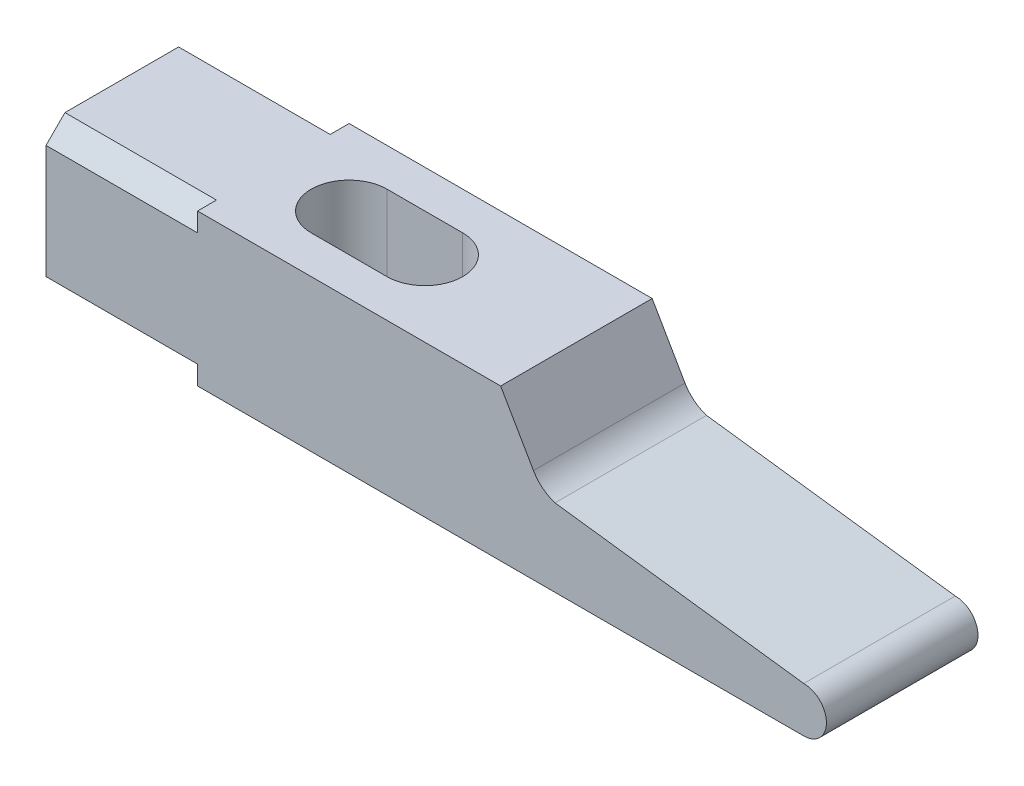
SolidWorks part; units mm, degrees
ref_plane "前视基准面" through (0, 0, 0) normal (0, 0, 1) x (1, 0, 0)
ref_plane "上视基准面" through (0, 0, 0) normal (0, 1, 0) x (1, 0, 0)
ref_plane "右视基准面" through (0, 0, 0) normal (1, 0, 0) x (0, 0, -1)
sketch "草图1" plane through (0, 0, 0) normal (0, 0, 1) x (1, 0, 0)
  line L0 (0, 0) -> (0, 20)
  line L1 (0, 20) -> (60, 20)
  line L2 (60, 20) -> (64.3301, 12.5)
  line L4 (100, 0) -> (0, 0)
  line L6 (67.1731, 10.2263) -> (100, 6)
  arc A0 (67.1731, 10.2263) -> (64.3301, 12.5) centre (68.6603, 15) cw
  arc A1 (100, 6) -> (100, 0) centre (100, 3) cw
  dimension "D5" = 5
  dimension "D1" = 20
  dimension "D2" = 60
  dimension "D3" = 100
  dimension "D4" = 120
  dimension "D6" = 15
extrude "凸台-拉伸1" add sketch "草图1" along normal mid plane 20
sketch "草图2" plane through (0, 20, 0) normal (0, 1, 0) x (1, 0, 0)
  line L0 (30, 0) -> (40, 0) construction
  line L1 (30, 5) -> (40, 5)
  line L2 (30, -5) -> (40, -5)
  line L3 (0, -10) -> (0, 10) construction
  arc A0 (30, 5) -> (30, -5) centre (30, 0) ccw
  arc A1 (40, -5) -> (40, 5) centre (40, 0) ccw
  point P3 (35, 0)
  dimension "D2" = 5
  dimension "D1" = 10
  dimension "D3" = 30
extrude "切除-拉伸1" cut sketch "草图2" against normal through all
sketch "草图3" plane through (0, 0, 0) normal (-1, 0, 0) x (0, 0, 1)
  line L0 (-7.5, 20) -> (-10, 17.5)
  line L1 (10, 20) -> (-10, 20) construction
  line L2 (-10, 20) -> (-10, 0) construction
  line L3 (10, 17.5) -> (7.5, 20)
  line L4 (7.5, 0) -> (10, 2.5)
  line L5 (-10, 2.5) -> (-7.5, 0)
  line L7 (-10, 20) -> (-10, 0)
  line L8 (-10, 0) -> (10, 0)
  line L9 (10, 0) -> (10, 20)
  line L10 (10, 20) -> (-10, 20)
  line L11 (-10, 20) -> (-10, 0)
  line L12 (-10, 0) -> (10, 0)
  line L13 (10, 0) -> (10, 20)
  line L14 (10, 20) -> (-10, 20)
  point P8 (0, 10)
  line M6 (-10, 20) -> (-10, 0)
  line M7 (-10, 0) -> (10, 0)
  line M8 (10, 0) -> (10, 20)
  line M9 (10, 20) -> (-10, 20)
  dimension "D2" = 45
  dimension "D3" = 2.5
  dimension "D1" = 0
  dimension "D4" = 4
extrude "切除-拉伸2" cut sketch "草图3" against normal blind 20 contours L0 M9 M6 | L3 M8 M9 | L4 M7 M8 | L5 M6 M7
